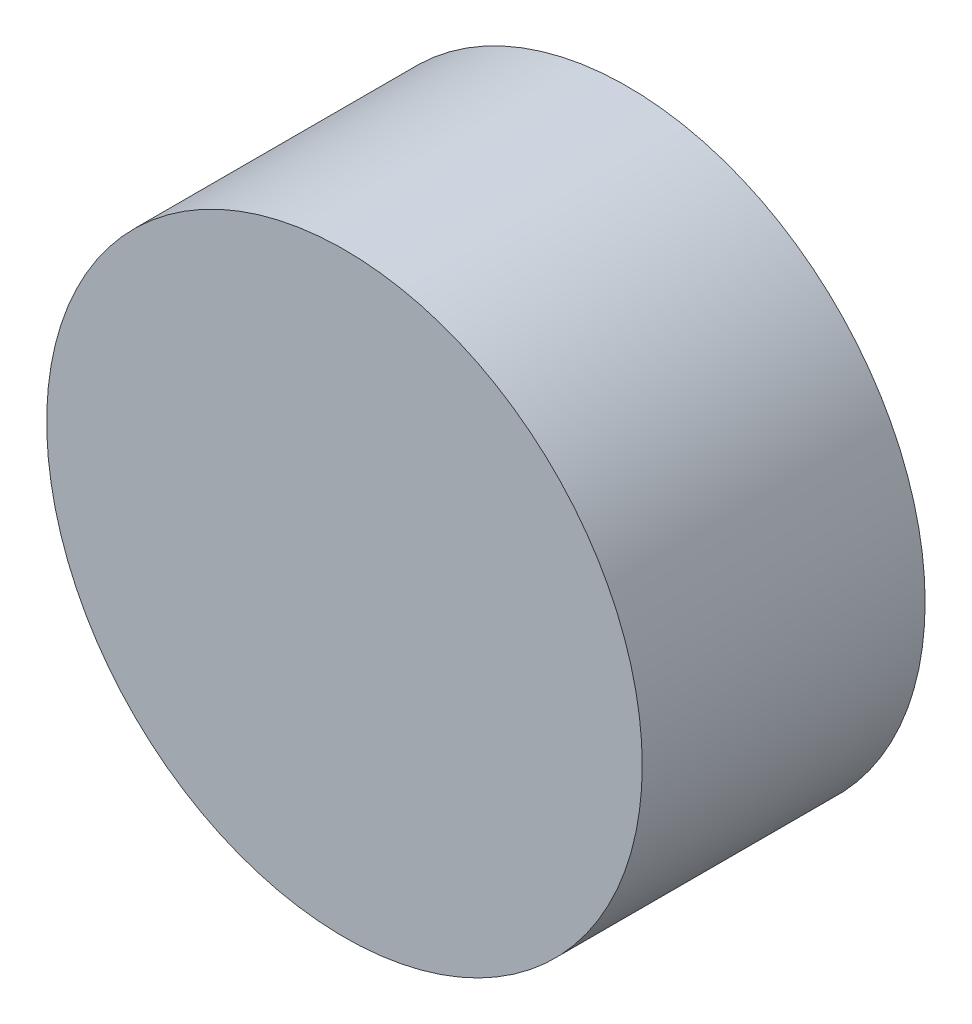
SolidWorks part; units mm, degrees
ref_plane "Płaszczyzna przednia" through (0, 0, 0) normal (0, 0, 1) x (1, 0, 0)
ref_plane "Płaszczyzna górna" through (0, 0, 0) normal (0, 1, 0) x (1, 0, 0)
ref_plane "Płaszczyzna prawa" through (0, 0, 0) normal (1, 0, 0) x (0, 0, -1)
sketch "Szkic1" plane through (0, 0, 0) normal (0, 0, 1) x (1, 0, 0)
  circle A0 centre (0, 0) radius 40
  dimension "D1" = 80
extrude "Dodanie-wyciągnięcie1" add sketch "Szkic1" along normal blind 38
